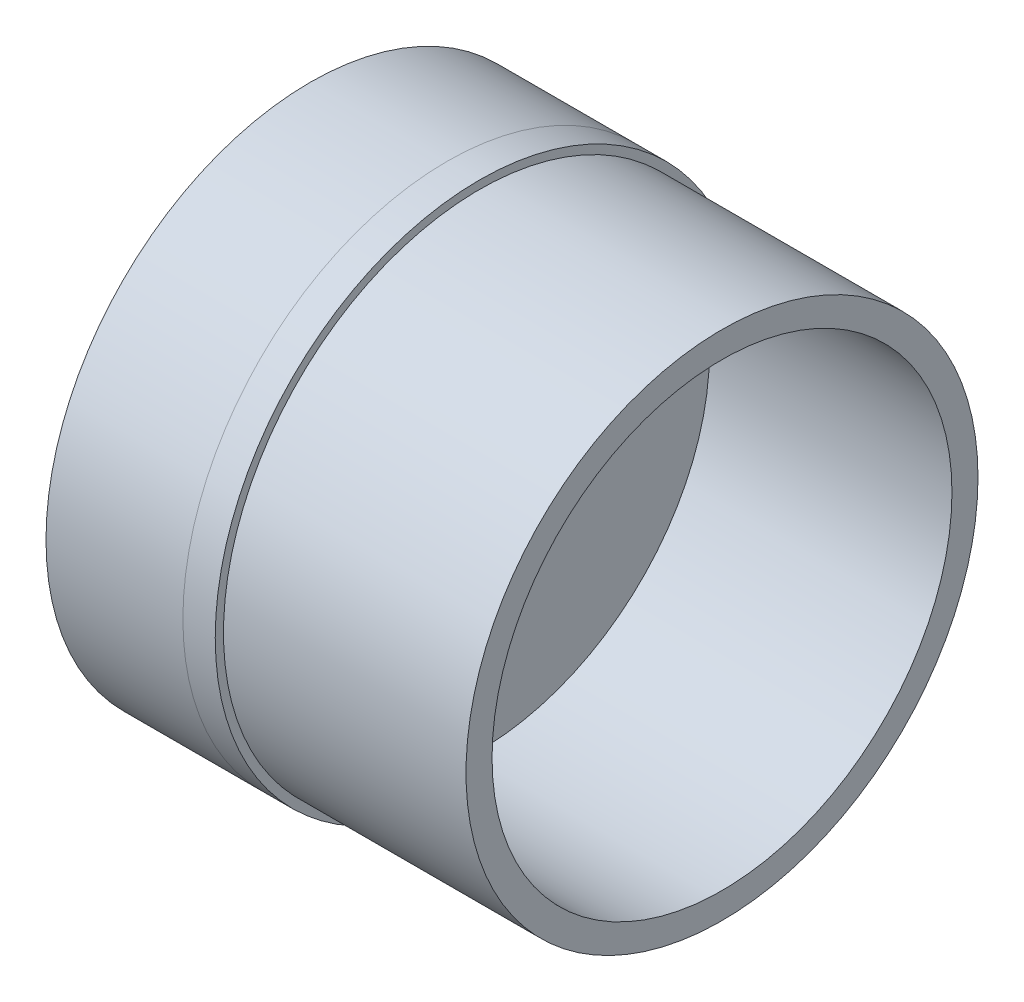
SolidWorks part; units mm, degrees
ref_plane "Front Plane" through (0, 0, 0) normal (1, 0, 0) x (0, 1, 0)
ref_plane "Top Plane" through (0, 0, 0) normal (0, 0, 1) x (0, 1, 0)
ref_plane "Right Plane" through (0, 0, 0) normal (0, 1, 0) x (-1, 0, 0)
sketch "Sketch1" plane through (0, 0, 0) normal (0, 0, 1) x (0, 1, 0)
  line L0 (0, 0) -> (0, 25.8273) construction
  line L1 (5, 6) -> (5, 0)
  line L2 (5, 0) -> (49.03, 0)
  line L4 (5, 6) -> (49.03, 6)
  line L5 (49.03, 0) -> (49.03, 6)
  line L6 (47.5, 0) -> (42.6688, 0)
  line L7 (47.5, 0) -> (47.5, -45)
  line L8 (47.5, -45) -> (42.6688, -45)
  line L9 (42.6688, 0) -> (42.6688, -45)
  dimension "D1" = 6
  dimension "D2" = 44.03
  dimension "D3" = 45
  dimension "D4" = 1.53
  dimension "D5" = 49.03
revolve "Revolve1" add sketch "Sketch1" angle 360 about L0
sketch "Sketch2" plane through (-6, 0, 0) normal (-1, 0, 0) x (0, -1, 0)
  circle A0 centre (0, 0) radius 5
  circle A1 centre (0, 0) radius 49.03
extrude "Boss-Extrude1" add sketch "Sketch2" along normal blind 25.4 separate body
